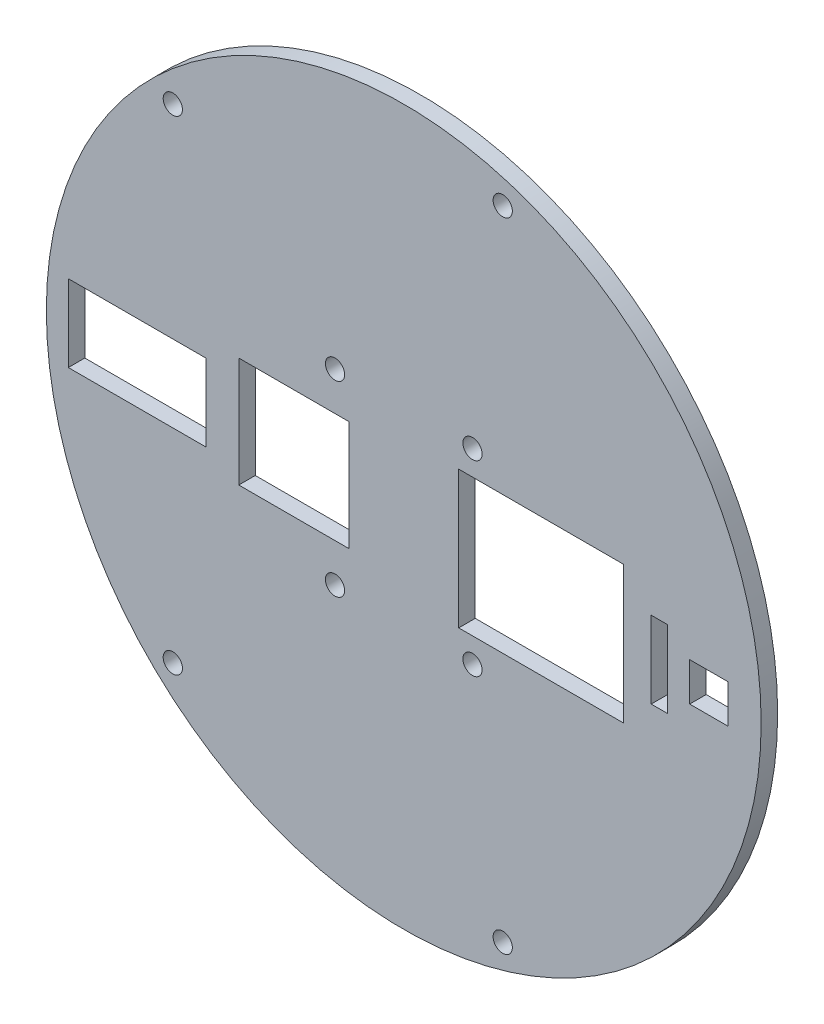
SolidWorks part; units mm, degrees
ref_plane "Alzado" through (0, 0, 0) normal (0, 0, 1) x (1, 0, 0)
ref_plane "Planta" through (0, 0, 0) normal (0, 1, 0) x (1, 0, 0)
ref_plane "Vista lateral" through (0, 0, 0) normal (1, 0, 0) x (0, 0, -1)
sketch "Croquis1" plane through (0, 0, 0) normal (0, 0, 1) x (1, 0, 0)
  line L0 (-65, 0) -> (65, 0) construction
  line L1 (0, 65) -> (0, -65) construction
  line L2 (-30, 10) -> (-10, 10)
  line L3 (-30, 10) -> (-30, -10)
  line L4 (-30, -10) -> (-10, -10)
  line L5 (-10, 10) -> (-10, -10)
  line L7 (-61, 7) -> (-36, 7)
  line L8 (-61, 7) -> (-61, -7)
  line L9 (-61, -7) -> (-36, -7)
  line L10 (-36, 7) -> (-36, -7)
  line L11 (10, 12.5) -> (40, 12.5)
  line L12 (10, 12.5) -> (10, -12.5)
  line L13 (10, -12.5) -> (40, -12.5)
  line L14 (40, 12.5) -> (40, -12.5)
  line L15 (45, 7) -> (48, 7)
  line L16 (45, 7) -> (45, -7)
  line L17 (45, -7) -> (48, -7)
  line L18 (48, 7) -> (48, -7)
  line L19 (52, 3.5) -> (59, 3.5)
  line L20 (52, 3.5) -> (52, -3.5)
  line L21 (52, -3.5) -> (59, -3.5)
  line L22 (59, 3.5) -> (59, -3.5)
  circle A0 centre (0, 0) radius 65
  circle A1 centre (-12.5, 17) radius 1.75
  circle A2 centre (12.5, 17) radius 1.75
  circle A3 centre (12.5, -17) radius 1.75
  circle A4 centre (-12.5, -17) radius 1.75
  dimension "D1" = 130
  dimension "D14" = 3.5
  dimension "D15" = 3.5
  dimension "D2" = 20
  dimension "D3" = 20
  dimension "D4" = 10
  dimension "D5" = 10
  dimension "D6" = 14
  dimension "D7" = 25
  dimension "D8" = 7
  dimension "D9" = 36
  dimension "D10" = 30
  dimension "D11" = 25
  dimension "D12" = 12.5
  dimension "D13" = 10
  dimension "D16" = 25
  dimension "D17" = 12.5
  dimension "D18" = 17
  dimension "D19" = 14
  dimension "D20" = 7
  dimension "D21" = 3
  dimension "D22" = 5
  dimension "D23" = 7
  dimension "D24" = 7
  dimension "D25" = 3.5
  dimension "D26" = 4
extrude "Saliente-Extruir1" add sketch "Croquis1" along normal blind 3
sketch "Croquis2" plane through (0, 0, 3) normal (0, 0, 1) x (1, 0, 0)
  line L0 (0, 0) -> (65, 0) construction
  circle A0 centre (-42, 44) radius 1.75
  circle A1 centre (18, 58) radius 1.75
  circle A2 centre (0, 0) radius 65 construction
  circle A3 centre (18, -58) radius 1.75
  circle A4 centre (-42, -44) radius 1.75
  dimension "D1" = 3.5
  dimension "D2" = 3.5
  dimension "D3" = 44
  dimension "D4" = 42
  dimension "D5" = 18
  dimension "D6" = 58
extrude "Cortar-Extruir1" cut sketch "Croquis2" against normal blind 3
